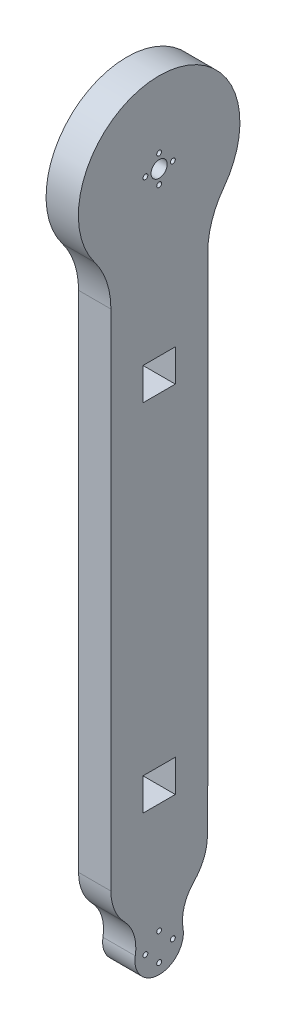
SolidWorks part; units mm, degrees
ref_plane "Front Plane" through (0, 0, 0) normal (0, 0, 1) x (1, 0, 0)
ref_plane "Top Plane" through (0, 0, 0) normal (0, 1, 0) x (1, 0, 0)
ref_plane "Right Plane" through (0, 0, 0) normal (1, 0, 0) x (0, 0, -1)
sketch "Sketch1" plane through (0, 0, 0) normal (1, 0, 0) x (0, 0, -1)
  line L0 (0, 109.2241) -> (0, -43.1034)
  line L1 (-30, 109.061) -> (-30, -42.8298)
  line L2 (78.3088, 28.9591) -> (-108.4312, 28.9591) construction
  line L3 (-15.0612, 186.7411) -> (-15.0612, -120.2051) construction
  line L4 (-20.0612, 88.9591) -> (-10.0612, 88.9591)
  line L5 (-10.0612, 88.9591) -> (-10.0612, 78.9591)
  line L6 (-10.0612, 78.9591) -> (-20.0612, 78.9591)
  line L7 (-20.0612, 78.9591) -> (-20.0612, 88.9591)
  line L8 (-10.0612, -21.0409) -> (-20.0612, -21.0409)
  line L9 (-10.0612, -31.0409) -> (-10.0612, -21.0409)
  line L10 (-20.0612, -21.0409) -> (-20.0612, -31.0409)
  line L11 (-20.0612, -31.0409) -> (-10.0612, -31.0409)
  arc A0 (4.9707, 124.1849) -> (-35.0319, 124.1034) centre (-15.0612, 139.1478) ccw
  arc A1 (-30, 109.061) -> (-35.0319, 124.1034) centre (-55, 109.061) ccw
  arc A2 (0, 109.2241) -> (4.9707, 124.1849) centre (25, 109.2241) cw
  arc A3 (0, -43.1034) -> (2.1428, -53.2301) centre (25, -43.1034) ccw
  arc A4 (-30, -42.8298) -> (-32.2127, -53.1126) centre (-55, -42.8298) cw
  arc A5 (2.1428, -53.2301) -> (-32.2127, -53.1126) centre (-15.0612, -60.8522) cw
  point P6 (-15.0612, 28.9591)
  point P24 (-15.0612, 88.9591)
  dimension "D2" = 50
  dimension "D4" = 10
  dimension "D1" = 200
  dimension "D3" = 30
  dimension "D5" = 10
  dimension "D6" = 50
extrude "Boss-Extrude1" add sketch "Sketch1" along normal blind 10
sketch "Sketch2" plane through (10, 0, 0) normal (1, 0, 0) x (0, 0, -1)
  line L0 (-20.5619, 139.1478) -> (-9.524, 139.1478) construction
  line L1 (-15.0612, 144.2562) -> (-15.0612, 133.8529) construction
  circle A1 centre (-15.0612, 143.3978) radius 0.75
  circle A2 centre (-19.3112, 139.1478) radius 0.75
  circle A3 centre (-10.8112, 139.1478) radius 0.75
  circle A4 centre (-15.0612, 134.8978) radius 0.75
  dimension "D2" = 1.5
  dimension "D3" = 1.5
  dimension "D4" = 1.5
  dimension "D5" = 1.5
extrude "Cut-Extrude1" cut sketch "Sketch2" against normal through all
sketch "Sketch3" plane through (10, 0, 0) normal (1, 0, 0) x (0, 0, -1)
  line L0 (-15.0612, -65.1022) -> (-15.0612, -73.6022) construction
  line L1 (-19.3112, -69.3522) -> (-10.8112, -69.3522) construction
  circle A0 centre (-19.3112, -69.3522) radius 0.75
  circle A4 centre (-15.0612, -65.1022) radius 0.75
  circle A5 centre (-10.8112, -69.3522) radius 0.75
  circle A6 centre (-15.0612, -73.6022) radius 0.75
  point P11 (-15.0612, -69.3522)
  point P12 (-15.0612, -69.3522)
  dimension "D1" = 8.5
  dimension "D7" = 1.5
  dimension "D8" = 1.5
  dimension "D9" = 1.5
  dimension "D6" = 8.5
extrude "Cut-Extrude2" cut sketch "Sketch3" against normal through all
sketch "Sketch4" plane through (10, 0, 0) normal (1, 0, 0) x (0, 0, -1)
  line L0 (-30, -33.7397) -> (-50.7126, -33.7397)
  line L1 (-30, -33.7397) -> (-30, -46.9561)
  line L2 (-30, 109.061) -> (-30, -42.8298) construction
  line L3 (-15.0612, -61.8522) -> (-15.1038, -61.8522)
  line L4 (-0.1223, -33.7397) -> (-0.1223, -46.9561)
  line L5 (-50.7126, -33.7397) -> (-50.7126, -86.6761)
  line L6 (-50.7126, -86.6761) -> (22.0376, -86.6761)
  line L7 (22.0376, -86.6761) -> (22.0376, -33.7397)
  line L8 (22.0376, -33.7397) -> (-0.1223, -33.7397)
  arc A0 (-22.4562, -68.1018) -> (-7.6661, -68.1018) centre (-15.0612, -69.3522) ccw
  arc A1 (-25.8031, -57.3205) -> (-30, -46.9561) centre (-15.1038, -46.9561) cw
  arc A2 (-22.4562, -68.1018) -> (-25.8031, -57.3205) centre (-34.7813, -66.0178) ccw
  arc A3 (-7.6661, -68.1018) -> (-4.3193, -57.3205) centre (4.6589, -66.0178) cw
  arc A4 (-4.3193, -57.3205) -> (-0.1223, -46.9561) centre (-15.0185, -46.9561) ccw
  line M13 (-30, 109.061) -> (-30, -42.8298)
  arc M14 (-30, -42.8298) -> (-32.2127, -53.1126) centre (-55, -42.8298) cw
  arc M15 (-32.2127, -53.1126) -> (2.1428, -53.2301) centre (-15.0612, -60.8522) ccw
  arc M16 (2.1428, -53.2301) -> (0, -43.1034) centre (25, -43.1034) cw
  line M17 (0, -43.1034) -> (0, 109.2241)
  dimension "D1" = 15
  dimension "D2" = 14.8962
  dimension "D3" = 25
extrude "Cut-Extrude5" cut sketch "Sketch4" against normal blind 10 contours L7 L8 L0 L5 L6 M17 M16 M15 M14 M13 | A4 A3 A0 A2 A1 L1 L8 L4 M14 M15 M16 M17
sketch "Sketch5" plane through (10, 0, 0) normal (1, 0, 0) x (0, 0, -1)
  line L0 (-15.0612, 143.3978) -> (-15.0612, 134.8978) construction
  circle A0 centre (-15.0612, 139.1478) radius 2.5
  dimension "D1" = 5
extrude "Cut-Extrude6" cut sketch "Sketch5" against normal through all
